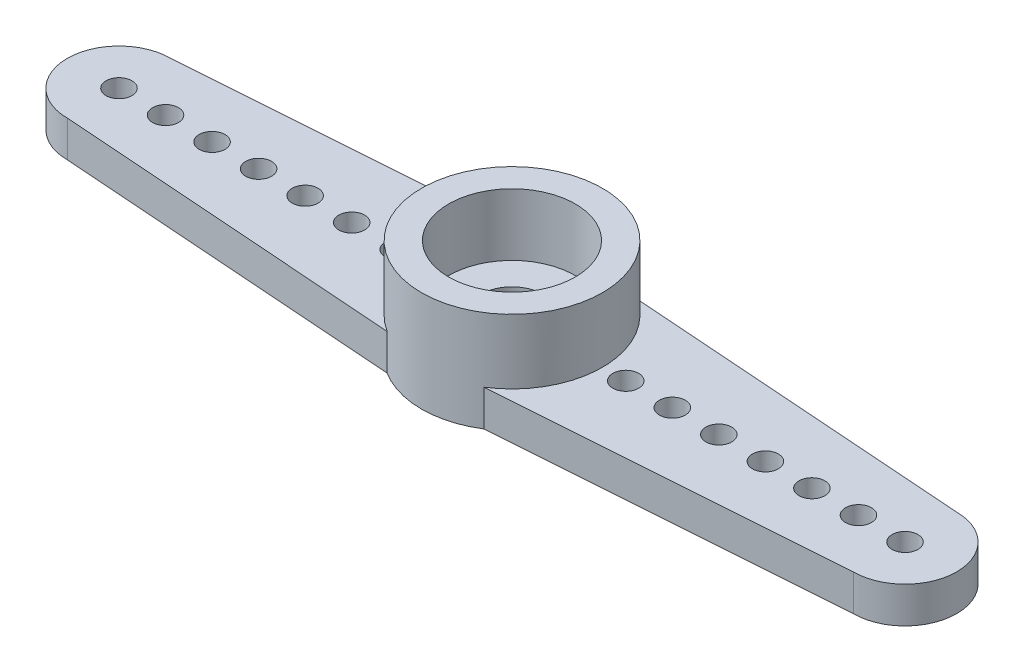
SolidWorks part; units mm, degrees
other "Camera1"
material "ABS"
ref_plane "Front Plane" through (0, 0, 0) normal (0, 0, 1) x (1, 0, 0)
ref_plane "Top Plane" through (0, 0, 0) normal (0, 1, 0) x (1, 0, 0)
ref_plane "Right Plane" through (0, 0, 0) normal (1, 0, 0) x (0, 0, -1)
sketch "Sketch1" plane through (0, 0, 0) normal (0, 1, 0) x (1, 0, 0)
  line L0 (-17.2, 0) -> (17.2, 0) construction
  line L1 (0, -8.35) -> (0, 8.35) construction
  line L2 (-15.2, 2) -> (-2, 2.95)
  line L3 (-15.2, -2) -> (-2, -2.95)
  line L4 (2, 6.35) -> (2, 3.5)
  line L5 (-2, 6.35) -> (-2, 2.95)
  line L6 (2, -6.35) -> (2, -3.5)
  line L7 (-2, -6.35) -> (-2, -2.95)
  line L8 (15.2, 2) -> (2, 3.5)
  line L9 (15.2, -2) -> (2, -3.5)
  circle A0 centre (0, 0) radius 3.5 construction
  arc A1 (-15.2, 2) -> (-15.2, -2) centre (-15.2, 0) ccw
  arc A2 (15.2, 2) -> (15.2, -2) centre (15.2, 0) cw
  arc A3 (2, 6.35) -> (-2, 6.35) centre (0, 6.35) ccw
  circle A4 centre (0, 6.35) radius 0.5
  circle A5 centre (0, 4.55) radius 0.5
  circle A6 centre (0, -4.55) radius 0.5
  circle A7 centre (0, -6.35) radius 0.5
  arc A8 (2, -6.35) -> (-2, -6.35) centre (0, -6.35) cw
  circle A10 centre (-15.2, 0) radius 0.5
  circle A11 centre (15.2, 0) radius 0.5
  circle A12 centre (-13.4, 0) radius 0.5
  circle A13 centre (-11.6, 0) radius 0.5
  circle A14 centre (-9.8, 0) radius 0.5
  circle A15 centre (-8, 0) radius 0.5
  circle A16 centre (-6.2, 0) radius 0.5
  circle A17 centre (-4.4, 0) radius 0.5
  circle A18 centre (13.4, 0) radius 0.5
  circle A19 centre (11.6, 0) radius 0.5
  circle A20 centre (9.8, 0) radius 0.5
  circle A21 centre (8, 0) radius 0.5
  circle A22 centre (6.2, 0) radius 0.5
  circle A23 centre (4.4, 0) radius 0.5
  point P5 (0, 0)
  point P8 (0, 0)
  point P25 (0, 6.85)
  point P26 (0, 4.05)
  dimension "D1" = 7
  dimension "D4" = 4
  dimension "D6" = 1
  dimension "D2" = 34.4
  dimension "D3" = 16.7
  dimension "D5" = 2
  dimension "D7" = 2.8
  dimension "D8" = 7
  dimension "D10" = 5.9
  dimension "D11" = 7
  dimension "D12" = 7
extrude "Boss-Extrude1" add sketch "Sketch1" along normal blind 1.4
sketch "Sketch2" plane through (0, 0, 0) normal (0, -1, 0) x (1, 0, 0)
  circle A0 centre (0, 0) radius 2.35
  dimension "D1" = 4.7
extrude "Cut-Extrude1" cut sketch "Sketch2" against normal blind 1
sketch "Sketch3" plane through (0, 1.4, 0) normal (0, 1, 0) x (1, 0, 0)
  circle A0 centre (0, 0) radius 2.45
  circle A1 centre (0, 0) radius 3.5
  dimension "D1" = 4.9
  dimension "D2" = 7
extrude "Boss-Extrude2" add sketch "Sketch3" along normal blind 2.5
sketch "Sketch4" plane through (0, 1.4, 0) normal (0, 1, 0) x (1, 0, 0)
  circle A0 centre (0, 0) radius 1.2
  dimension "D1" = 2.4
extrude "Cut-Extrude2" cut sketch "Sketch4" against normal through all
sketch "Sketch5" plane through (0, 1.4, 0) normal (0, 1, 0) x (1, 0, 0)
  circle A0 centre (0, 0) radius 1.2 construction
  circle A1 centre (0, 0) radius 2.45
  circle A2 centre (0, 0) radius 2.45
  circle A3 centre (0, 0) radius 1.2
  dimension "D1" = 0
extrude "Boss-Extrude3" add sketch "Sketch5" along normal blind 0.1
sketch "Sketch6" plane through (0, 0, 0) normal (0, -1, 0) x (1, 0, 0)
  line L0 (-2, -2.95) -> (-15.2, -2) construction
  line L1 (-1.8686, -2.9595) -> (-15.2, -2)
  line L2 (-15.2, 2) -> (-2, 2.95) construction
  line L3 (-15.2, 2) -> (-1.8686, 2.9595)
  line L4 (0, -9.3016) -> (0, 8.6978) construction
  line L5 (1.8686, -2.9595) -> (15.2, -2)
  line L6 (15.2, 2) -> (1.8686, 2.9595)
  line L8 (-17.8676, -8.836) -> (17.8676, -8.836)
  line L9 (-17.8676, -8.836) -> (-17.8676, 8.836)
  line L10 (-17.8676, 8.836) -> (17.8676, 8.836)
  line L11 (17.8676, -8.836) -> (17.8676, 8.836)
  line L12 (-17.8676, -8.836) -> (17.8676, 8.836) construction
  line L13 (-17.8676, 8.836) -> (17.8676, -8.836) construction
  arc A0 (-15.2, 2) -> (-15.2, -2) centre (-15.2, 0) ccw construction
  arc A1 (-15.2, 2) -> (-15.2, -2) centre (-15.2, 0) ccw
  circle A2 centre (0, 0) radius 3.5 construction
  arc A3 (1.8686, 2.9595) -> (-1.8686, 2.9595) centre (0, 0) ccw
  arc A4 (15.2, 2) -> (15.2, -2) centre (15.2, 0) cw
  arc A5 (-1.8686, -2.9595) -> (1.8686, -2.9595) centre (0, 0) ccw
extrude "Cut-Extrude4" cut sketch "Sketch6" against normal through all
